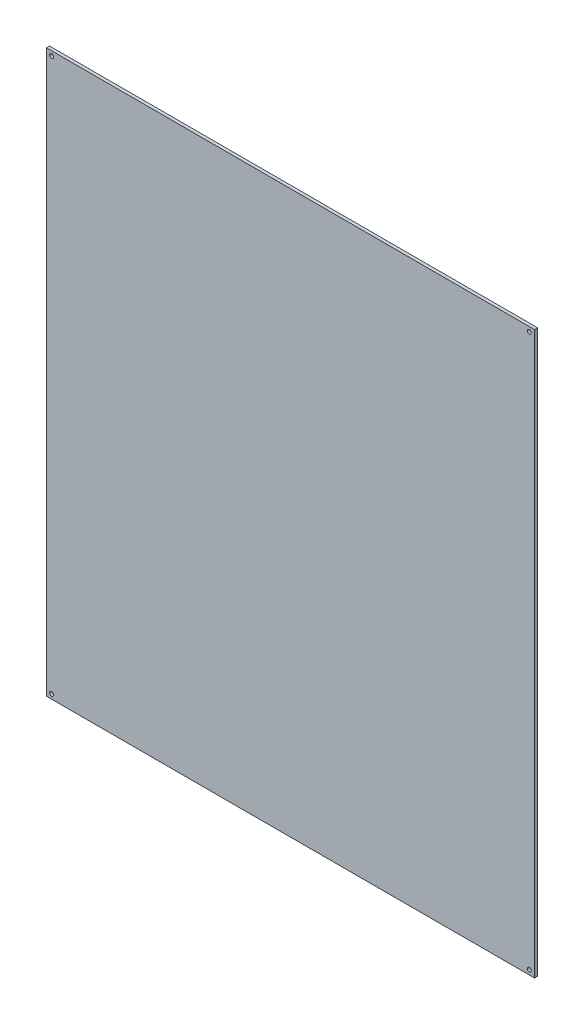
SolidWorks part; units mm, degrees
ref_plane "Piano frontale" through (0, 0, 0) normal (0, 0, 1) x (1, 0, 0)
ref_plane "Piano superiore" through (0, 0, 0) normal (0, 1, 0) x (1, 0, 0)
ref_plane "Piano destro" through (0, 0, 0) normal (1, 0, 0) x (0, 0, -1)
ref_plane "Piano1" through (0, 0, 5) normal (0, 0, 1) x (1, 0, 0)
sketch "Schizzo1" plane through (0, 0, 5) normal (0, 0, 1) x (1, 0, 0)
  line L4 (677.5, -197.5) -> (677.5, 718.5)
  line L5 (677.5, 718.5) -> (-118.5, 718.5)
  line L6 (-118.5, 718.5) -> (-118.5, -197.5)
  line L7 (-118.5, -197.5) -> (677.5, -197.5)
  circle A0 centre (-110, -190) radius 3.25
  circle A1 centre (-110, 711) radius 3.25
  circle A2 centre (669, 711) radius 3.25
  circle A3 centre (669, -190) radius 3.25
  dimension "D1" = 796
  dimension "D2" = 8.5
  dimension "D3" = 8.5
  dimension "D4" = 916
  dimension "D5" = 7.5
  dimension "D6" = 7.5
extrude "Estrusione-Estrusione1" add sketch "Schizzo1" against normal blind 5
